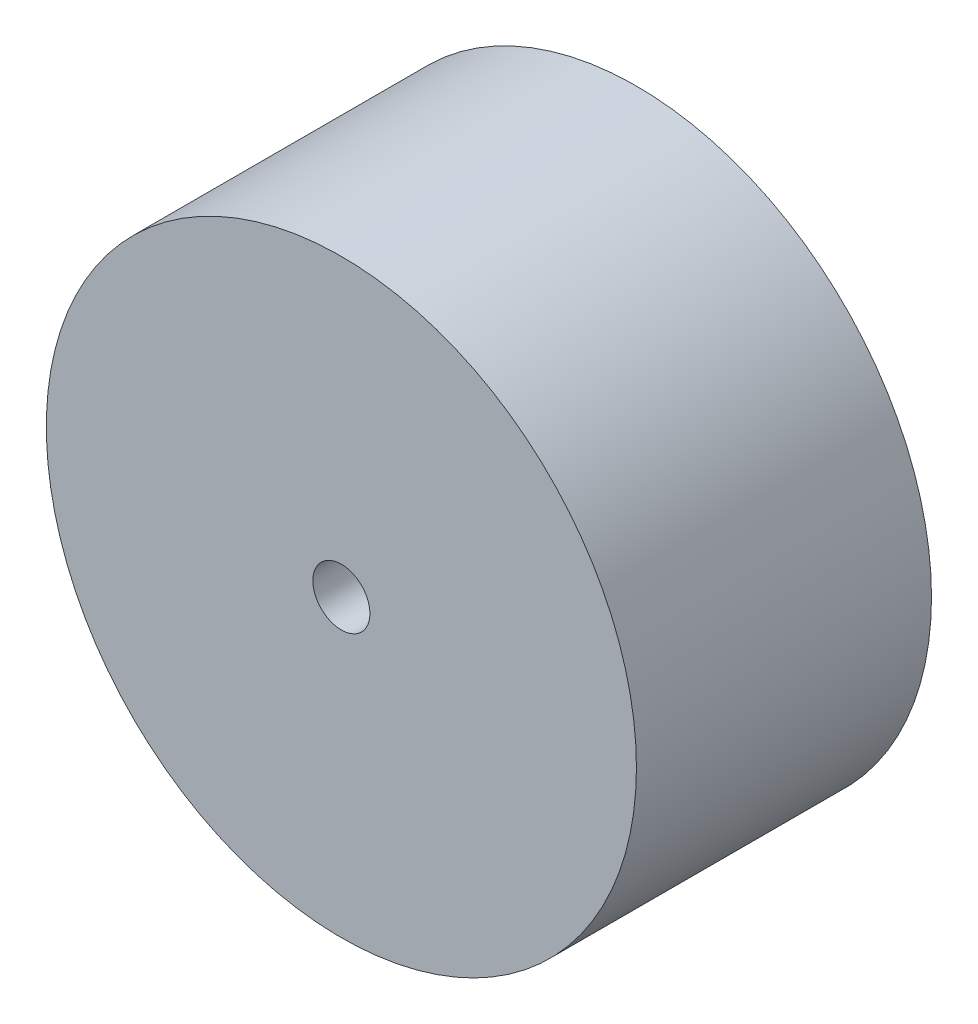
SolidWorks part; units mm, degrees
ref_plane "Płaszczyzna przednia" through (0, 0, 0) normal (0, 0, 1) x (1, 0, 0)
ref_plane "Płaszczyzna górna" through (0, 0, 0) normal (0, 1, 0) x (1, 0, 0)
ref_plane "Płaszczyzna prawa" through (0, 0, 0) normal (1, 0, 0) x (0, 0, -1)
sketch "Szkic1" plane through (0, 0, 0) normal (0, 0, 1) x (1, 0, 0)
  circle A0 centre (0, 0) radius 15
  circle A1 centre (0, 0) radius 1.45
  dimension "D1" = 30
  dimension "D2" = 2.9
extrude "Dodanie-wyciągnięcie1" add sketch "Szkic1" along normal blind 15
